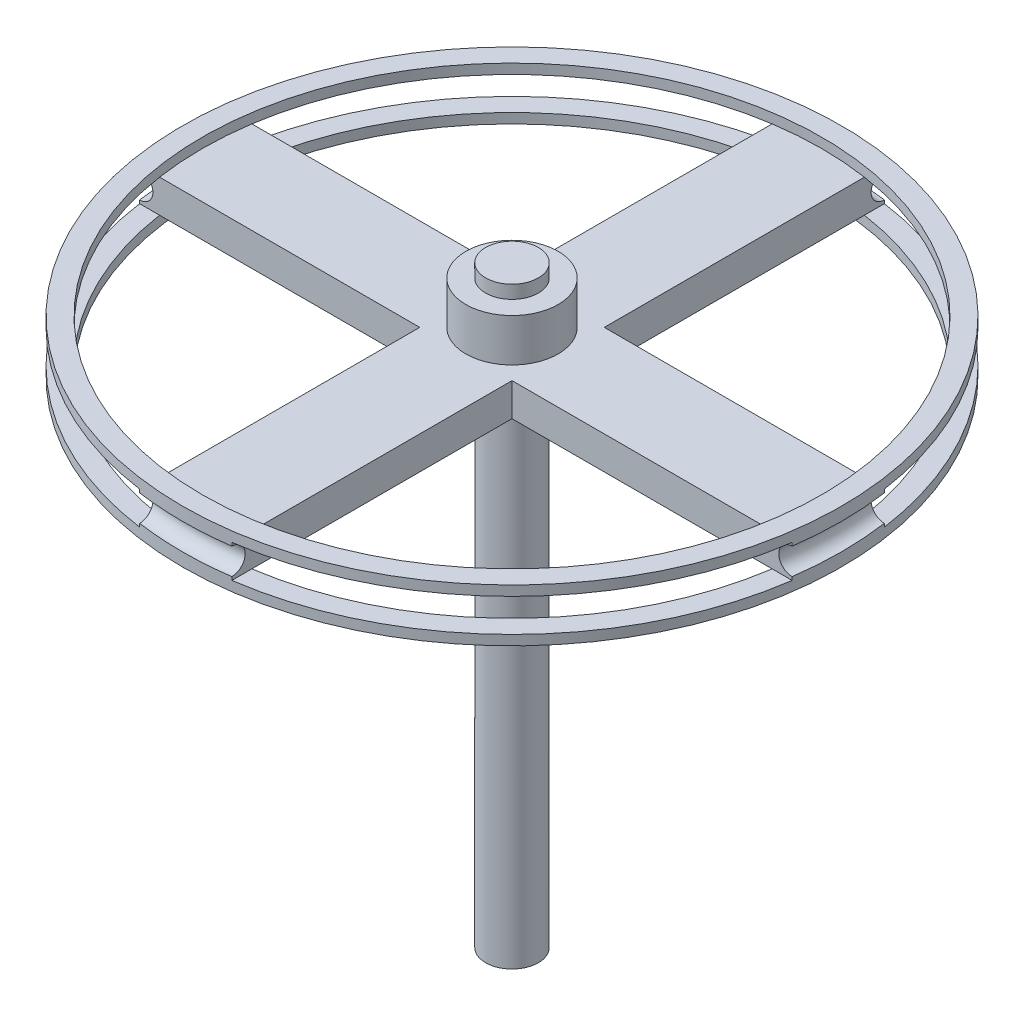
SolidWorks part; units mm, degrees
ref_plane "Front Plane" through (0, 0, 0) normal (0, 0, 1) x (1, 0, 0)
ref_plane "Top Plane" through (0, 0, 0) normal (0, 1, 0) x (1, 0, 0)
ref_plane "Right Plane" through (0, 0, 0) normal (1, 0, 0) x (0, 0, -1)
sketch "Sketch1" plane through (0, 0, 0) normal (0, 0, 1) x (1, 0, 0)
  line L0 (0, 60.3176) -> (0, -81.789) construction
  line L1 (8, 8) -> (8, -8)
  line L2 (8, 18) -> (8, 8)
  line L3 (14, -5) -> (14, -8)
  line L4 (8, -8) -> (14, -8)
  line L5 (100, 8) -> (100, 4)
  line L6 (14, 5) -> (94, 5)
  line L7 (100, -4) -> (100, -8)
  line L8 (14, -5) -> (94, -5)
  line L9 (14, 18) -> (14, 8)
  line L10 (14, 8) -> (14, 5)
  line L11 (94, 8) -> (94, 5)
  line L14 (94, 8) -> (100, 8)
  line L15 (94, -8) -> (100, -8)
  line L16 (94, -5) -> (94, -8)
  line L17 (8, 18) -> (14, 18)
  arc A0 (100, 4) -> (100, -4) centre (100, 0) ccw
  dimension "D1" = 3
  dimension "D2" = 94
  dimension "D3" = 10
  dimension "D4" = 6
  dimension "D6" = 8
  dimension "D7" = 6
revolve "Revolve2" add sketch "Sketch1" angle 360 about L0
sketch "Sketch2" plane through (0, 5, 0) normal (0, 1, 0) x (1, 0, 0)
  line L0 (14, 14) -> (14, 173.4359)
  line L1 (-173.4359, -14) -> (-14, -14)
  line L2 (-14, 14) -> (-14, 173.4359)
  line L3 (-173.4359, 14) -> (-14, 14)
  line L4 (14, 14) -> (173.4359, 14)
  line L8 (-14, -173.4359) -> (-14, -14)
  line L9 (14, -14) -> (173.4359, -14)
  line L10 (14, -173.4359) -> (14, -14)
  arc A0 (-14, 173.4359) -> (-173.4359, 14) centre (0, 0) ccw
  arc A2 (-173.4359, -14) -> (-14, -173.4359) centre (0, 0) ccw
  arc A3 (173.4359, 14) -> (14, 173.4359) centre (0, 0) ccw
  arc A4 (14, -173.4359) -> (173.4359, -14) centre (0, 0) ccw
extrude "Cut-Extrude1" cut sketch "Sketch2" against normal up to surface (10 mm away) up to face at (0, -5, 94)
sketch "Sketch3" plane through (0, -8, 0) normal (0, -1, 0) x (1, 0, 0)
  circle A0 centre (0, 0) radius 8
extrude "Boss-Extrude1" add sketch "Sketch3" along normal blind 150 and the other way blind 30
